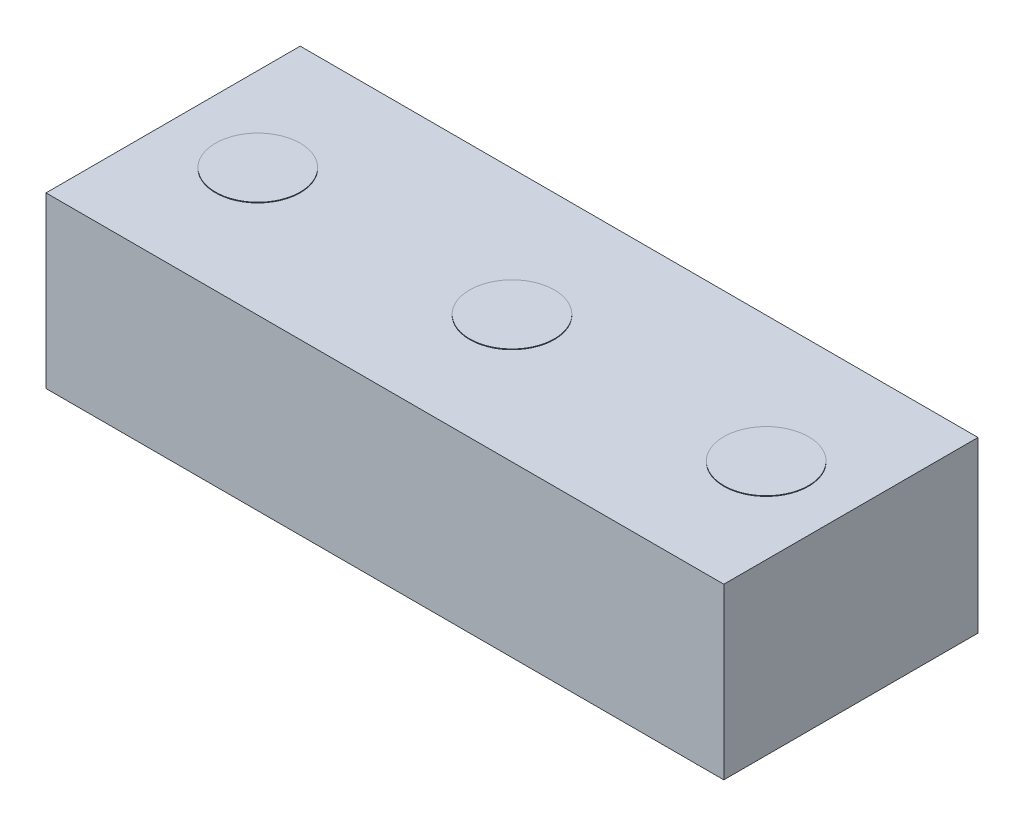
SolidWorks part; units mm, degrees
ref_plane "前视基准面" through (0, 0, 0) normal (0, 0, 1) x (1, 0, 0)
ref_plane "上视基准面" through (0, 0, 0) normal (0, 1, 0) x (1, 0, 0)
ref_plane "右视基准面" through (0, 0, 0) normal (1, 0, 0) x (0, 0, -1)
other "Configuration Table"
sketch "草图1" plane through (0, 0, 0) normal (0, 1, 0) x (1, 0, 0)
  line L1 (-200, -75) -> (200, -75)
  line L2 (-200, -75) -> (-200, 75)
  line L3 (-200, 75) -> (200, 75)
  line L4 (200, -75) -> (200, 75)
  line L5 (-200, -75) -> (200, 75) construction
  line L6 (-200, 75) -> (200, -75) construction
  point P0 (0, 0)
  dimension "D1" = 400
  dimension "D2" = 150
extrude "拉伸-薄壁1" add sketch "草图1" along normal blind 100 thin thin type one direction reverse wall 2.5
sketch "草图2" plane through (0, 100, 0) normal (0, 1, 0) x (1, 0, 0)
  line L4 (-200, -75) -> (200, -75)
  line L5 (200, -75) -> (200, 75)
  line L6 (200, 75) -> (-200, 75)
  line L7 (-200, 75) -> (-200, -75)
  line L8 (-200, -75) -> (200, -75)
  line L9 (200, -75) -> (200, 75)
  line L10 (200, 75) -> (-200, 75)
  line L11 (-200, 75) -> (-200, -75)
  dimension "D1" = 0
extrude "凸台-拉伸1" add sketch "草图2" against normal blind 2.5 contours L8 L9 L10 L11
sketch "草图3" plane through (0, 100, 0) normal (0, 1, 0) x (1, 0, 0)
  line L0 (0, 75) -> (0, -75) construction
  line L1 (200, 75) -> (-200, 75) construction
  line L2 (-200, -75) -> (200, -75) construction
  line L3 (200, 0) -> (-200, 0) construction
  line L4 (200, -75) -> (200, 75) construction
  line L5 (-200, 75) -> (-200, -75) construction
  circle A0 centre (0, 0) radius 25
  circle A1 centre (150, 0) radius 25
  circle A2 centre (-150, 0) radius 25
  dimension "D1" = 50
  dimension "D3" = 150
  dimension "D2" = 2
extrude "凸台-拉伸2" add sketch "草图3" along normal blind 0.4 separate body
